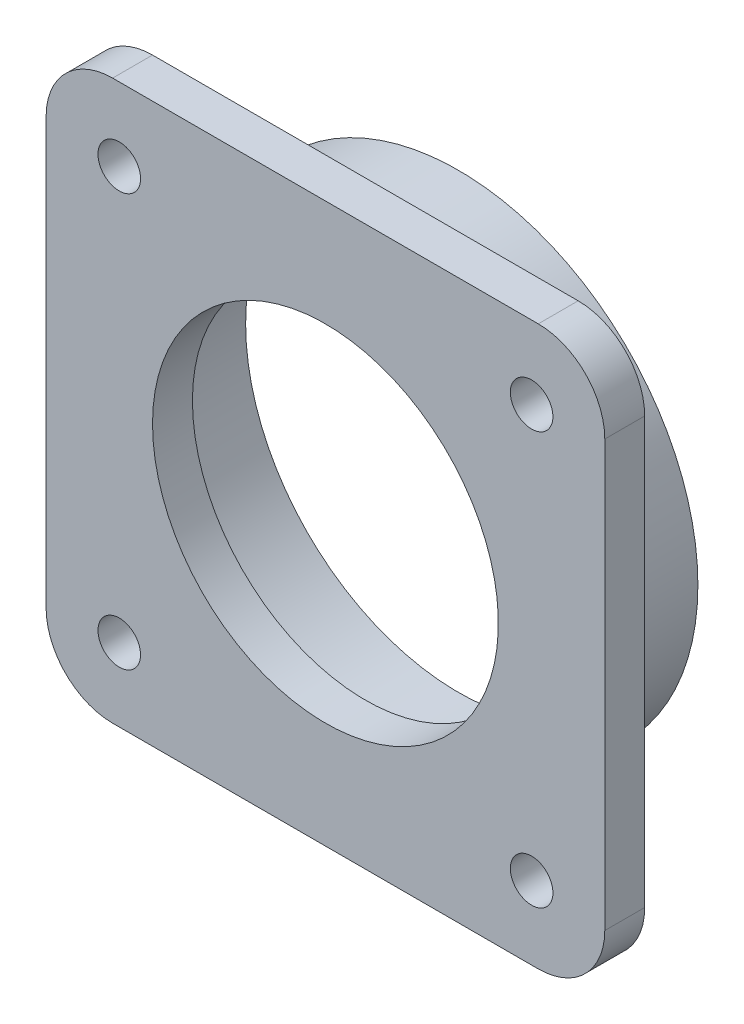
SolidWorks part; units mm, degrees
ref_plane "前视基准面" through (0, 0, 0) normal (0, 0, 1) x (1, 0, 0)
ref_plane "上视基准面" through (0, 0, 0) normal (0, 1, 0) x (1, 0, 0)
ref_plane "右视基准面" through (0, 0, 0) normal (1, 0, 0) x (0, 0, -1)
other "Configuration Table"
sketch "草图1" plane through (0, 0, 0) normal (0, 0, 1) x (1, 0, 0)
  line L1 (-21, -21) -> (21, -21)
  line L2 (-21, -21) -> (-21, 21)
  line L3 (-21, 21) -> (21, 21)
  line L4 (21, -21) -> (21, 21)
  line L5 (-21, -21) -> (21, 21) construction
  line L6 (-21, 21) -> (21, -21) construction
  line L7 (-15.5, -15.5) -> (15.5, -15.5)
  line L8 (-15.5, -15.5) -> (-15.5, 15.5)
  line L9 (-15.5, 15.5) -> (15.5, 15.5)
  line L10 (15.5, -15.5) -> (15.5, 15.5)
  line L11 (-15.5, -15.5) -> (15.5, 15.5) construction
  line L12 (-15.5, 15.5) -> (15.5, -15.5) construction
  circle A0 centre (-15.5, 15.5) radius 1.6
  circle A1 centre (15.5, 15.5) radius 1.6
  circle A2 centre (15.5, -15.5) radius 1.6
  circle A3 centre (-15.5, -15.5) radius 1.6
  circle A4 centre (0, 0) radius 11
  point P0 (0, 0)
  point P6 (0, 0)
  point P21 (0, 0)
  dimension "D4" = 3.2
  dimension "D6" = 22
  dimension "D1" = 42
  dimension "D2" = 42
  dimension "D3" = 31
  dimension "D5" = 4
extrude "凸台-拉伸1" add sketch "草图1" along normal blind 3 contours A3 L7 A2 L10 A1 L9 A0 L8 A4 | L1 L4 L3 L2 A3 L8 A0 L9 A1 L10 A2 L7
fillet "圆角1" radius 5 4 edges at (-21, -21, 1.5) (21, -21, 1.5) (21, 21, 1.5) (-21, 21, 1.5)
sketch "草图2" plane through (0, 0, 0) normal (0, 0, -1) x (-1, 0, 0)
  circle A0 centre (0, 0) radius 16
  circle A1 centre (0, 0) radius 18
  dimension "D1" = 32
  dimension "D2" = 2
extrude "凸台-拉伸2" add sketch "草图2" along normal blind 7
sketch "草图3" plane through (0, 0, 0) normal (0, 0, -1) x (-1, 0, 0)
  circle A0 centre (0, 0) radius 13
  dimension "D1" = 26
extrude "切除-拉伸1" cut sketch "草图3" against normal blind 3
